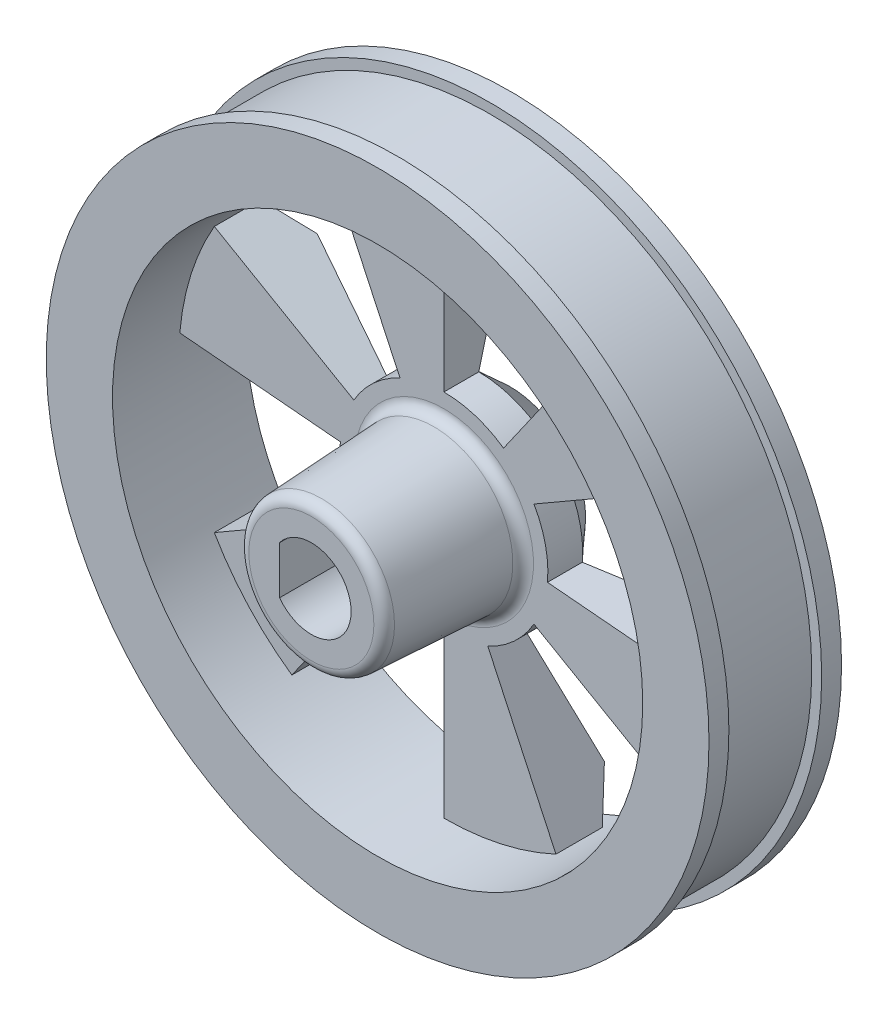
SolidWorks part; units mm, degrees
ref_plane "Front Plane" through (0, 0, 0) normal (0, 0, 1) x (1, 0, 0)
ref_plane "Top Plane" through (0, 0, 0) normal (0, 1, 0) x (1, 0, 0)
ref_plane "Right Plane" through (0, 0, 0) normal (1, 0, 0) x (0, 0, -1)
sketch "Sketch1" plane through (0, 0, 0) normal (1, 0, 0) x (0, 0, -1)
  line L0 (0, 0) -> (28.2857, 0) construction
  line L1 (0, 0) -> (0, 22.5) construction
  line L2 (3.5, 25) -> (5, 25)
  line L3 (-5, 25) -> (-3.5, 25)
  line L4 (-5, 25) -> (-5, 20)
  line L5 (-5, 20) -> (0, 20)
  line L6 (5, 25) -> (5, 20)
  line L7 (-5, 25) -> (5, 20) construction
  line L8 (-5, 20) -> (5, 25) construction
  line L10 (-3.5, 25) -> (-3.5, 24.25)
  line L11 (-3.5, 24.25) -> (3.5, 24.25)
  line L12 (3.5, 25) -> (3.5, 24.25)
  line L13 (3.5, 20) -> (5, 16.8162)
  line L14 (5, 16.8162) -> (2.6264, 7.8442)
  line L15 (2.6264, 7.8442) -> (5, 5.6912)
  line L16 (5, 5.6912) -> (5, 0)
  line L17 (5, 0) -> (0, 0)
  line L18 (0, 0) -> (0, 20)
  line L20 (3.5, 20) -> (5, 20)
  dimension "D1" = 22.5
  dimension "D2" = 5
  dimension "D3" = 10
  dimension "D4" = 1.5
  dimension "D5" = 1.5
revolve "Revolve1" add sketch "Sketch1" angle 360 about L0
sketch "Sketch4" plane through (0, 0, -5) normal (0, 0, -1) x (-1, 0, 0)
  line L0 (0, -7.8442) -> (0, -20)
  line L1 (4.4993, -6.4256) -> (11.4715, -16.383)
  circle A0 centre (0, 0) radius 7.8442 construction
  circle A1 centre (0, 0) radius 20 construction
  arc A2 (0, -7.8442) -> (4.4993, -6.4256) centre (0, 0) ccw
  arc A3 (0, -20) -> (11.4715, -16.383) centre (0, 0) ccw
  dimension "D3" = 35
extrude "Cut-Extrude1" cut sketch "Sketch4" against normal through all
pattern_circular "CirPattern1" count 6 over 360 about axis through (0, 0, 0) along (0, 0, 1) of "Cut-Extrude1"
sketch "Sketch5" plane through (0, 0, 0) normal (0, 0, 1) x (1, 0, 0)
  circle A0 centre (0, 0) radius 6
  dimension "D1" = 12
extrude "Boss-Extrude1" add sketch "Sketch5" along normal blind 10 draft 3
fillet "Fillet1" radius 0.8 2 edges at (-6, 0, 0) (5.4759, 0, 10)
sketch "Sketch6" plane through (0, 0, 10) normal (0, 0, 1) x (1, 0, 0)
  line L0 (-2.4, 1.8) -> (-2.4, -1.8)
  line L1 (3, 0) -> (3, -3.441) construction
  arc A0 (-2.4, -1.8) -> (-2.4, 1.8) centre (0, 0) ccw
  dimension "D1" = 6
  dimension "D2" = 5.4
extrude "Cut-Extrude2" cut sketch "Sketch6" against normal blind 10
